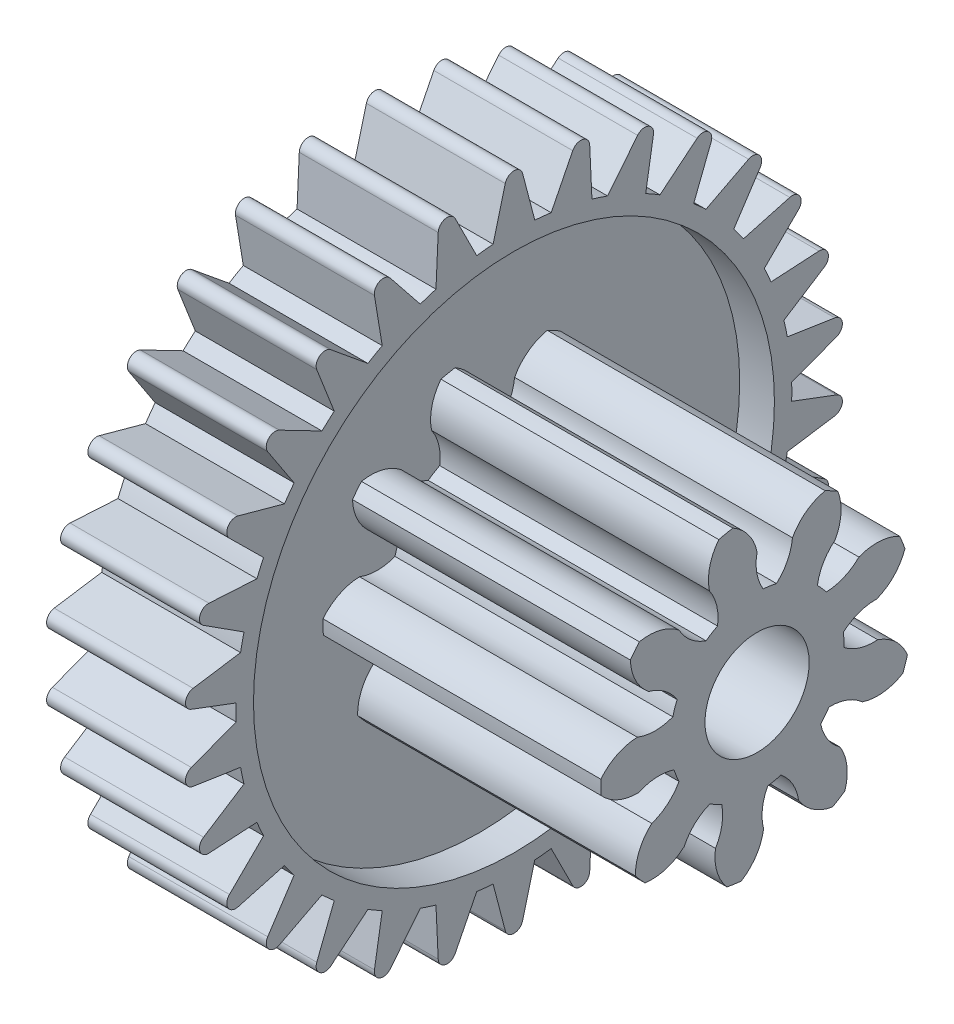
SolidWorks part; units mm, degrees
ref_plane "Front Plane" through (0, 0, 0) normal (0, 0, 1) x (1, 0, 0)
ref_plane "Top Plane" through (0, 0, 0) normal (0, 1, 0) x (1, 0, 0)
ref_plane "Right Plane" through (0, 0, 0) normal (1, 0, 0) x (0, 0, -1)
sketch "Sketch1" plane through (0, 0, 0) normal (1, 0, 0) x (0, 0, -1)
  line L0 (0, 0) -> (0, 15.1561) construction
  line L1 (0.6, 7.9775) -> (0.25, 9.3154)
  line L2 (-0.6, 7.9775) -> (-0.25, 9.3154)
  line L3 (2.2455, 7.6784) -> (2.1813, 9.0599)
  line L4 (1.0717, 7.9279) -> (1.6922, 9.1638)
  line L5 (3.7929, 7.0437) -> (4.0173, 8.4084)
  line L6 (2.6966, 7.5318) -> (3.5605, 8.6117)
  line L7 (5.1744, 6.1012) -> (5.6777, 7.3894)
  line L8 (4.2036, 6.8066) -> (5.2732, 7.6833)
  line L9 (6.3299, 4.8921) -> (7.09, 6.0474)
  line L10 (5.5269, 5.7839) -> (6.7554, 6.419)
  line L11 (7.2087, 3.4691) -> (8.1924, 4.4412)
  line L12 (6.6087, 4.5083) -> (7.9424, 4.8742)
  line L13 (7.7724, 1.8945) -> (8.9367, 2.6409)
  line L14 (7.4016, 3.0358) -> (8.7822, 3.1164)
  line L15 (7.9965, 0.2372) -> (9.2905, 0.7251)
  line L16 (7.871, 1.4306) -> (9.2382, 1.2224)
  line L17 (7.871, -1.4306) -> (9.2382, -1.2224)
  line L18 (7.9965, -0.2372) -> (9.2905, -0.7251)
  line L19 (7.4016, -3.0358) -> (8.7822, -3.1164)
  line L20 (7.7724, -1.8945) -> (8.9367, -2.6409)
  line L21 (6.6087, -4.5083) -> (7.9424, -4.8742)
  line L22 (7.2087, -3.4691) -> (8.1924, -4.4412)
  line L23 (5.5269, -5.7839) -> (6.7554, -6.419)
  line L24 (6.3299, -4.8921) -> (7.09, -6.0474)
  line L25 (4.2036, -6.8066) -> (5.2732, -7.6833)
  line L26 (5.1744, -6.1012) -> (5.6777, -7.3894)
  line L27 (2.6966, -7.5318) -> (3.5605, -8.6117)
  line L28 (3.7929, -7.0437) -> (4.0173, -8.4084)
  line L29 (1.0717, -7.9279) -> (1.6922, -9.1638)
  line L30 (2.2455, -7.6784) -> (2.1813, -9.0599)
  line L31 (-0.6, -7.9775) -> (-0.25, -9.3154)
  line L32 (0.6, -7.9775) -> (0.25, -9.3154)
  line L33 (-2.2455, -7.6784) -> (-2.1813, -9.0599)
  line L34 (-1.0717, -7.9279) -> (-1.6922, -9.1638)
  line L35 (-3.7929, -7.0437) -> (-4.0173, -8.4084)
  line L36 (-2.6966, -7.5318) -> (-3.5605, -8.6117)
  line L37 (-5.1744, -6.1012) -> (-5.6777, -7.3894)
  line L38 (-4.2036, -6.8066) -> (-5.2732, -7.6833)
  line L39 (-6.3299, -4.8921) -> (-7.09, -6.0474)
  line L40 (-5.5269, -5.7839) -> (-6.7554, -6.419)
  line L41 (-7.2087, -3.4691) -> (-8.1924, -4.4412)
  line L42 (-6.6087, -4.5083) -> (-7.9424, -4.8742)
  line L43 (-7.7724, -1.8945) -> (-8.9367, -2.6409)
  line L44 (-7.4016, -3.0358) -> (-8.7822, -3.1164)
  line L45 (-7.9965, -0.2372) -> (-9.2905, -0.7251)
  line L46 (-7.871, -1.4306) -> (-9.2382, -1.2224)
  line L47 (-7.871, 1.4306) -> (-9.2382, 1.2224)
  line L48 (-7.9965, 0.2372) -> (-9.2905, 0.7251)
  line L49 (-7.4016, 3.0358) -> (-8.7822, 3.1164)
  line L50 (-7.7724, 1.8945) -> (-8.9367, 2.6409)
  line L51 (-6.6087, 4.5083) -> (-7.9424, 4.8742)
  line L52 (-7.2087, 3.4691) -> (-8.1924, 4.4412)
  line L53 (-5.5269, 5.7839) -> (-6.7554, 6.419)
  line L54 (-6.3299, 4.8921) -> (-7.09, 6.0474)
  line L55 (-4.2036, 6.8066) -> (-5.2732, 7.6833)
  line L56 (-5.1744, 6.1012) -> (-5.6777, 7.3894)
  line L57 (-2.6966, 7.5318) -> (-3.5605, 8.6117)
  line L58 (-3.7929, 7.0437) -> (-4.0173, 8.4084)
  line L59 (-1.0717, 7.9279) -> (-1.6922, 9.1638)
  line L60 (-2.2455, 7.6784) -> (-2.1813, 9.0599)
  circle A0 centre (0, 0) radius 7.5
  arc A2 (0.25, 9.3154) -> (-0.25, 9.3154) centre (0, 9.25) ccw
  arc A4 (2.1813, 9.0599) -> (1.6922, 9.1638) centre (1.9232, 9.0479) ccw
  arc A6 (4.0173, 8.4084) -> (3.5605, 8.6117) centre (3.7623, 8.4503) ccw
  arc A8 (5.6777, 7.3894) -> (5.2732, 7.6833) centre (5.437, 7.4834) ccw
  arc A10 (7.09, 6.0474) -> (6.7554, 6.419) centre (6.8741, 6.1895) ccw
  arc A12 (8.1924, 4.4412) -> (7.9424, 4.8742) centre (8.0107, 4.625) ccw
  arc A14 (8.9367, 2.6409) -> (8.7822, 3.1164) centre (8.7973, 2.8584) ccw
  arc A16 (9.2905, 0.7251) -> (9.2382, 1.2224) centre (9.1993, 0.9669) ccw
  arc A18 (9.2382, -1.2224) -> (9.2905, -0.7251) centre (9.1993, -0.9669) ccw
  arc A20 (8.7822, -3.1164) -> (8.9367, -2.6409) centre (8.7973, -2.8584) ccw
  arc A22 (7.9424, -4.8742) -> (8.1924, -4.4412) centre (8.0107, -4.625) ccw
  arc A24 (6.7554, -6.419) -> (7.09, -6.0474) centre (6.8741, -6.1895) ccw
  arc A26 (5.2732, -7.6833) -> (5.6777, -7.3894) centre (5.437, -7.4834) ccw
  arc A28 (3.5605, -8.6117) -> (4.0173, -8.4084) centre (3.7623, -8.4503) ccw
  arc A30 (1.6922, -9.1638) -> (2.1813, -9.0599) centre (1.9232, -9.0479) ccw
  arc A32 (-0.25, -9.3154) -> (0.25, -9.3154) centre (0, -9.25) ccw
  arc A34 (-2.1813, -9.0599) -> (-1.6922, -9.1638) centre (-1.9232, -9.0479) ccw
  arc A36 (-4.0173, -8.4084) -> (-3.5605, -8.6117) centre (-3.7623, -8.4503) ccw
  arc A38 (-5.6777, -7.3894) -> (-5.2732, -7.6833) centre (-5.437, -7.4834) ccw
  arc A40 (-7.09, -6.0474) -> (-6.7554, -6.419) centre (-6.8741, -6.1895) ccw
  arc A42 (-8.1924, -4.4412) -> (-7.9424, -4.8742) centre (-8.0107, -4.625) ccw
  arc A44 (-8.9367, -2.6409) -> (-8.7822, -3.1164) centre (-8.7973, -2.8584) ccw
  arc A46 (-9.2905, -0.7251) -> (-9.2382, -1.2224) centre (-9.1993, -0.9669) ccw
  arc A48 (-9.2382, 1.2224) -> (-9.2905, 0.7251) centre (-9.1993, 0.9669) ccw
  arc A50 (-8.7822, 3.1164) -> (-8.9367, 2.6409) centre (-8.7973, 2.8584) ccw
  arc A52 (-7.9424, 4.8742) -> (-8.1924, 4.4412) centre (-8.0107, 4.625) ccw
  arc A54 (-6.7554, 6.419) -> (-7.09, 6.0474) centre (-6.8741, 6.1895) ccw
  arc A56 (-5.2732, 7.6833) -> (-5.6777, 7.3894) centre (-5.437, 7.4834) ccw
  arc A58 (-3.5605, 8.6117) -> (-4.0173, 8.4084) centre (-3.7623, 8.4503) ccw
  arc A60 (-1.6922, 9.1638) -> (-2.1813, 9.0599) centre (-1.9232, 9.0479) ccw
  arc A61 (-2.2455, 7.6784) -> (-2.6966, 7.5318) centre (0, 0) ccw
  arc A64 (-3.7929, 7.0437) -> (-4.2036, 6.8066) centre (0, 0) ccw
  arc A66 (-5.1744, 6.1012) -> (-5.5269, 5.7839) centre (0, 0) ccw
  arc A67 (-6.3299, 4.8921) -> (-6.6087, 4.5083) centre (0, 0) ccw
  arc A70 (-7.2087, 3.4691) -> (-7.4016, 3.0358) centre (0, 0) ccw
  arc A71 (-7.7724, 1.8945) -> (-7.871, 1.4306) centre (0, 0) ccw
  arc A74 (-7.9965, 0.2372) -> (-7.9965, -0.2372) centre (0, 0) ccw
  arc A75 (-7.871, -1.4306) -> (-7.7724, -1.8945) centre (0, 0) ccw
  arc A78 (-7.4016, -3.0358) -> (-7.2087, -3.4691) centre (0, 0) ccw
  arc A80 (-6.6087, -4.5083) -> (-6.3299, -4.8921) centre (0, 0) ccw
  arc A82 (-5.5269, -5.7839) -> (-5.1744, -6.1012) centre (0, 0) ccw
  arc A84 (-4.2036, -6.8066) -> (-3.7929, -7.0437) centre (0, 0) ccw
  arc A86 (-2.6966, -7.5318) -> (-2.2455, -7.6784) centre (0, 0) ccw
  arc A88 (-1.0717, -7.9279) -> (-0.6, -7.9775) centre (0, 0) ccw
  arc A90 (0.6, -7.9775) -> (1.0717, -7.9279) centre (0, 0) ccw
  arc A92 (2.2455, -7.6784) -> (2.6966, -7.5318) centre (0, 0) ccw
  arc A94 (3.7929, -7.0437) -> (4.2036, -6.8066) centre (0, 0) ccw
  arc A95 (5.1744, -6.1012) -> (5.5269, -5.7839) centre (0, 0) ccw
  arc A98 (6.3299, -4.8921) -> (6.6087, -4.5083) centre (0, 0) ccw
  arc A99 (7.2087, -3.4691) -> (7.4016, -3.0358) centre (0, 0) ccw
  arc A102 (7.7724, -1.8945) -> (7.871, -1.4306) centre (0, 0) ccw
  arc A104 (7.9965, -0.2372) -> (7.9965, 0.2372) centre (0, 0) ccw
  arc A105 (-0.6, 7.9775) -> (-1.0717, 7.9279) centre (0, 0) ccw
  arc A106 (1.0717, 7.9279) -> (0.6, 7.9775) centre (0, 0) ccw
  arc A107 (2.6966, 7.5318) -> (2.2455, 7.6784) centre (0, 0) ccw
  arc A108 (4.2036, 6.8066) -> (3.7929, 7.0437) centre (0, 0) ccw
  arc A109 (7.871, 1.4306) -> (7.7724, 1.8945) centre (0, 0) ccw
  arc A110 (7.4016, 3.0358) -> (7.2087, 3.4691) centre (0, 0) ccw
  arc A111 (6.6087, 4.5083) -> (6.3299, 4.8921) centre (0, 0) ccw
  arc A112 (5.5269, 5.7839) -> (5.1744, 6.1012) centre (0, 0) ccw
  point P156 (0, 0)
  dimension "D1" = 15
  dimension "D2" = 8
  dimension "D5" = 0.2584
  dimension "D3" = 1.2
  dimension "D4" = 0.25
  dimension "D6" = 30
extrude "Boss-Extrude1" add sketch "Sketch1" along normal blind 4
sketch "Sketch2" plane through (0, 0, 0) normal (1, 0, 0) x (0, 0, -1)
  circle A0 centre (0, 0) radius 1.5
  circle A1 centre (0, 0) radius 2.5
  dimension "D1" = 3
  dimension "D2" = 5
extrude "Boss-Extrude2" add sketch "Sketch2" along normal blind 11 separate body
sketch "Sketch3" plane through (0, 0, 0) normal (1, 0, 0) x (0, 0, -1)
  circle A0 centre (0, 0) radius 2.5 construction
  circle A1 centre (0, 0) radius 2.5
  circle A2 centre (0, 0) radius 7.5 construction
  circle A3 centre (0, 0) radius 7.5
extrude "Boss-Extrude3" add sketch "Sketch3" along normal blind 1 from offset 2
sketch "Sketch4" plane through (3, 0, 0) normal (1, 0, 0) x (0, 0, -1)
  circle A0 centre (0, 0) radius 3.5
  circle A4 centre (0, 0) radius 4.5
  circle A5 centre (0, 0) radius 2.5 construction
  circle A6 centre (0, 0) radius 2.5
  circle A7 centre (0, 3.5) radius 1.4
  circle A8 centre (1.3717, 3.22) radius 1.4
  circle A9 centre (-1.3717, 3.22) radius 1.4
  circle A10 centre (-2.524, 2.4248) radius 1.4
  circle M2 centre (0, 0) radius 2.5
  dimension "D1" = 7
  dimension "D2" = 9
  dimension "D3" = 2.8
extrude "Boss-Extrude4" add sketch "Sketch4" along normal up to surface (8 mm away) separate body contours A0 A9 A4 A7 | A10 A7 A9 A8 A0 M2 | A10 A7 M2 | A9 A6 A8
pattern_circular "CirPattern1" count 9 over 360 about axis through (0, 0, 0) along (1, 0, 0) of "Boss-Extrude4"
combine bodies "Combine2" bodies to combine 107 105
